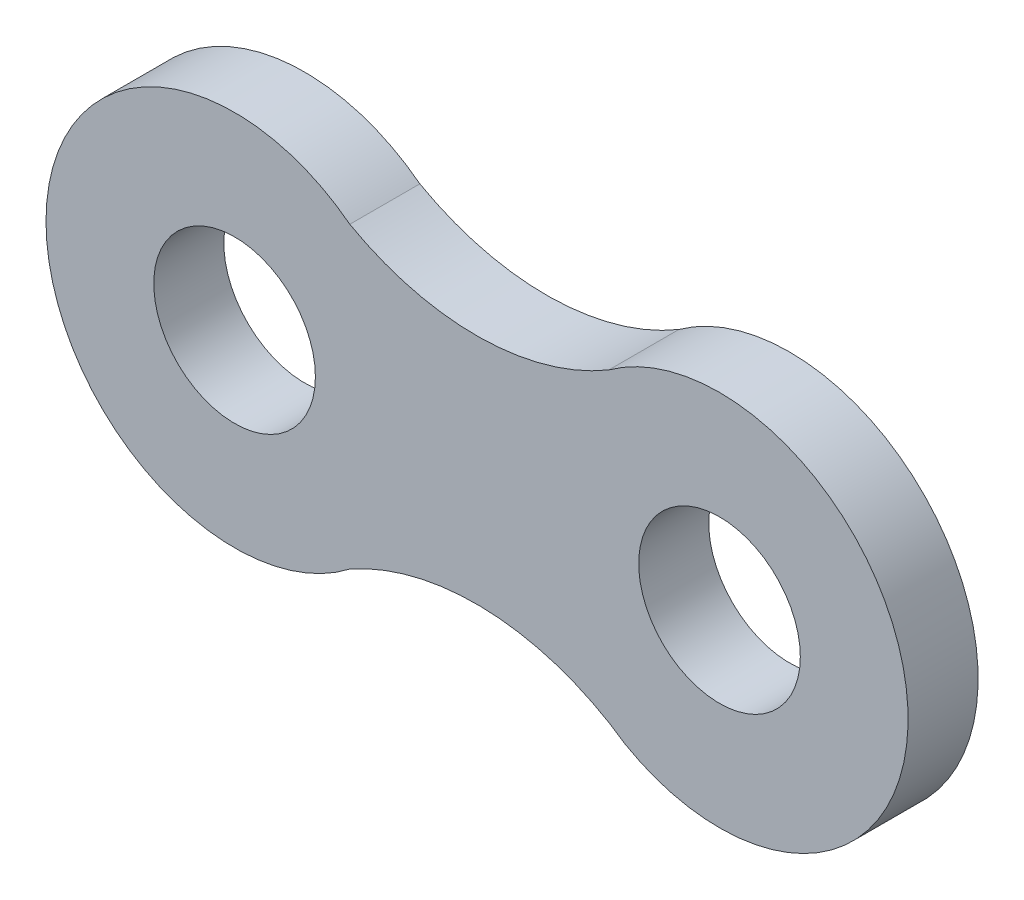
SolidWorks part; units mm, degrees
ref_plane "前视基准面" through (0, 0, 0) normal (0, 0, 1) x (1, 0, 0)
ref_plane "上视基准面" through (0, 0, 0) normal (0, 1, 0) x (1, 0, 0)
ref_plane "右视基准面" through (0, 0, 0) normal (1, 0, 0) x (0, 0, -1)
sketch "草图1" plane through (0, 0, 0) normal (0, 0, 1) x (1, 0, 0)
  line L1 (-44.817, 0) -> (-35.817, 0) construction
  arc A0 (-42.6785, 2.7706) -> (-42.6785, -2.7706) centre (-44.817, 0) ccw
  arc A1 (-37.5662, -3.0316) -> (-37.871, 2.8339) centre (-35.817, 0) ccw
  arc A2 (-42.6785, 2.7706) -> (-37.871, 2.8339) centre (-40.3295, 6.9593) ccw
  arc A3 (-42.6785, -2.7706) -> (-37.5662, -3.0316) centre (-40.3295, -6.9593) cw
  circle A4 centre (-35.817, 0) radius 1.5
  circle A5 centre (-44.817, 0) radius 1.5
  dimension "D1" = 7
  dimension "D2" = 7
  dimension "D4" = 3
  dimension "D5" = 3
  dimension "D3" = 9
extrude "拉伸1" add sketch "草图1" along normal blind 1.3
